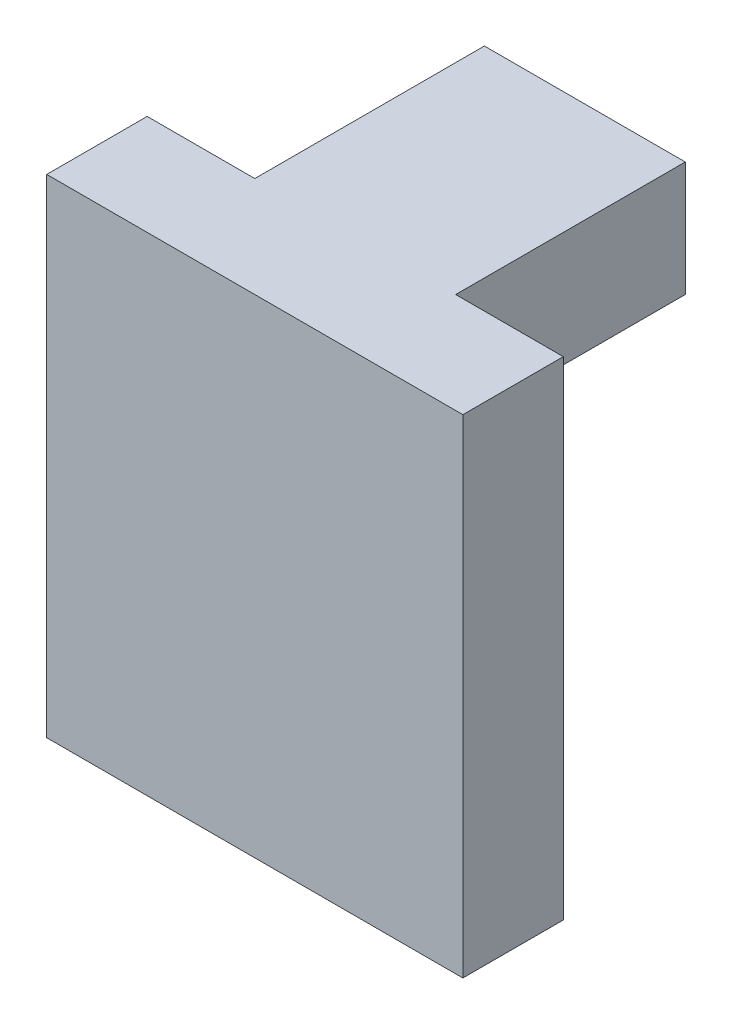
SolidWorks part; units mm, degrees
ref_plane "前视基准面" through (0, 0, 0) normal (0, 0, 1) x (1, 0, 0)
ref_plane "上视基准面" through (0, 0, 0) normal (0, 1, 0) x (1, 0, 0)
ref_plane "右视基准面" through (0, 0, 0) normal (1, 0, 0) x (0, 0, -1)
other "Configuration Table"
sketch "草图1" plane through (0, 0, 0) normal (0, 0, 1) x (1, 0, 0)
  line L1 (-14.5, -17) -> (14.5, -17)
  line L2 (-14.5, -17) -> (-14.5, 17)
  line L3 (-14.5, 17) -> (14.5, 17)
  line L4 (14.5, -17) -> (14.5, 17)
  line L5 (-14.5, -17) -> (14.5, 17) construction
  line L6 (-14.5, 17) -> (14.5, -17) construction
  point P0 (0, 0)
  dimension "D1" = 29
  dimension "D2" = 34
extrude "凸台-拉伸1" add sketch "草图1" along normal blind 7
sketch "草图3" plane through (0, 0, 0) normal (0, 0, -1) x (-1, 0, 0)
  line L0 (-14.5, 17) -> (14.5, 17) construction
  line L1 (-7, 17) -> (7, 17)
  line L2 (-7, 17) -> (-7, 9)
  line L3 (-7, 9) -> (7, 9)
  line L4 (7, 17) -> (7, 9)
  line L5 (0, 0) -> (0, 9) construction
  dimension "D1" = 14
  dimension "D2" = 8
extrude "凸台-拉伸2" add sketch "草图3" along normal blind 16
